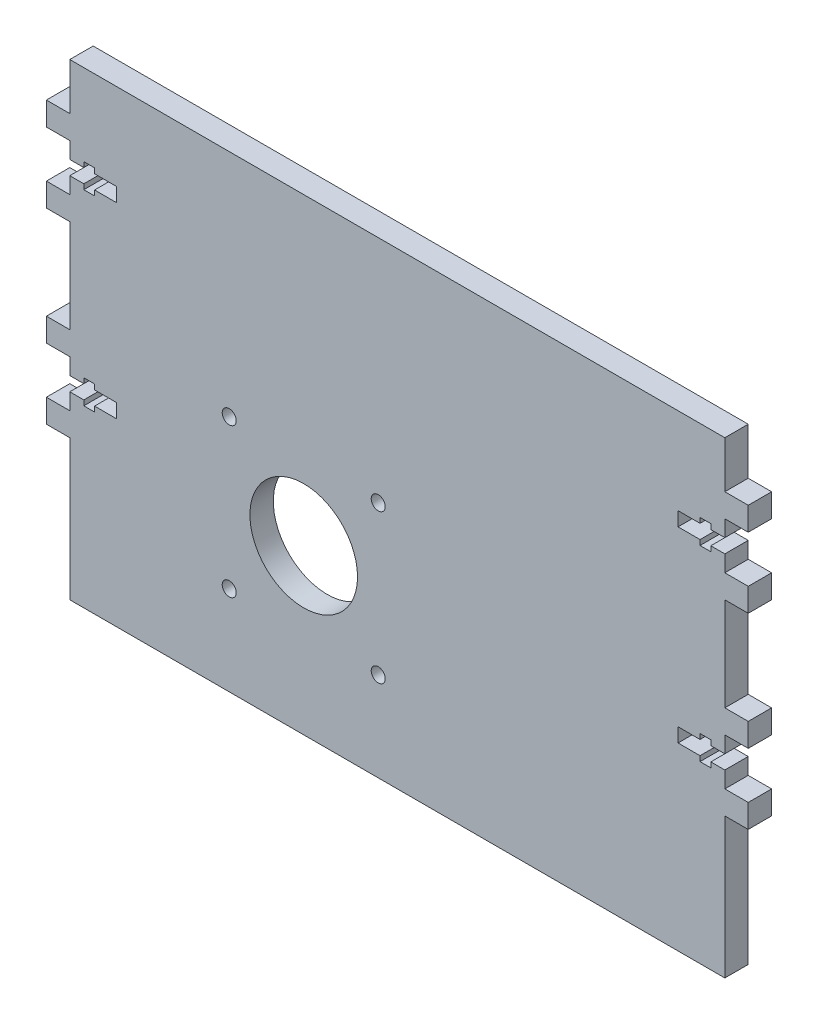
SolidWorks part; units mm, degrees
ref_plane "Front Plane" through (0, 0, 0) normal (0, 0, 1) x (1, 0, 0)
ref_plane "Top Plane" through (0, 0, 0) normal (0, 1, 0) x (1, 0, 0)
ref_plane "Right Plane" through (0, 0, 0) normal (1, 0, 0) x (0, 0, -1)
sketch "Sketch1" plane through (0, 0, 0) normal (0, 0, 1) x (1, 0, 0)
  line L0 (0, 0) -> (0, 100) construction
  line L1 (0, 100) -> (-140, 100)
  line L4 (-70, 68.7693) -> (-70, -10.9046) construction
  line L5 (0, 60) -> (-37.6147, 60) construction
  line L6 (0, 80) -> (-11.2208, 80) construction
  line L7 (0, 78.5) -> (0, 75)
  line L8 (5, 75) -> (5, 70)
  line L9 (5, 70) -> (0, 70)
  line L10 (5, 75) -> (0, 75)
  line L11 (0, 81.5) -> (0, 85)
  line L12 (0, 85) -> (5, 85)
  line L13 (5, 85) -> (5, 90)
  line L14 (5, 90) -> (0, 90)
  line L15 (0, 78.5) -> (0, 81.5) construction
  line L16 (0, 81.5) -> (-3, 81.5)
  line L17 (-5.3, 81.5) -> (-5.3, 82.6)
  line L18 (-3, 77.4) -> (-5.3, 77.4)
  line L19 (-3, 82.6) -> (-3, 81.5)
  line L20 (-5.3, 81.5) -> (-10, 81.5)
  line L21 (-10, 81.5) -> (-10, 78.5)
  line L22 (-10, 78.5) -> (-5.3, 78.5)
  line L23 (-3, 78.5) -> (-3, 77.4)
  line L24 (-5.3, 82.6) -> (-3, 82.6)
  line L25 (-5.3, 77.4) -> (-5.3, 78.5)
  line L26 (-3, 78.5) -> (0, 78.5)
  line L27 (-10, 80) -> (0, 80) construction
  line L66 (-145, 90) -> (-140, 90)
  line L67 (-145, 85) -> (-145, 90)
  line L68 (-140, 85) -> (-145, 85)
  line L69 (-140, 81.5) -> (-140, 85)
  line L70 (-140, 81.5) -> (-137, 81.5)
  line L71 (-137, 82.6) -> (-137, 81.5)
  line L72 (-134.7, 82.6) -> (-137, 82.6)
  line L73 (-134.7, 81.5) -> (-134.7, 82.6)
  line L74 (-134.7, 81.5) -> (-130, 81.5)
  line L75 (-130, 81.5) -> (-130, 78.5)
  line L76 (-130, 78.5) -> (-134.7, 78.5)
  line L77 (-134.7, 77.4) -> (-134.7, 78.5)
  line L78 (-137, 77.4) -> (-134.7, 77.4)
  line L79 (-137, 78.5) -> (-137, 77.4)
  line L80 (-137, 78.5) -> (-140, 78.5)
  line L81 (-140, 78.5) -> (-140, 75)
  line L82 (-145, 75) -> (-140, 75)
  line L83 (-145, 75) -> (-145, 70)
  line L84 (-145, 70) -> (-140, 70)
  line L85 (-140, 100) -> (-140, 90)
  line L90 (0, 90) -> (0, 100)
  line L91 (-145, 50) -> (-140, 50)
  line L92 (-145, 45) -> (-145, 50)
  line L93 (-145, 45) -> (-140, 45)
  line L94 (-140, 41.5) -> (-140, 45)
  line L95 (-137, 41.5) -> (-140, 41.5)
  line L96 (-137, 41.5) -> (-137, 42.6)
  line L97 (-137, 42.6) -> (-134.7, 42.6)
  line L98 (-134.7, 42.6) -> (-134.7, 41.5)
  line L99 (-130, 41.5) -> (-134.7, 41.5)
  line L100 (-130, 38.5) -> (-130, 41.5)
  line L101 (-134.7, 38.5) -> (-130, 38.5)
  line L102 (-134.7, 38.5) -> (-134.7, 37.4)
  line L103 (-134.7, 37.4) -> (-137, 37.4)
  line L104 (-137, 37.4) -> (-137, 38.5)
  line L105 (-140, 38.5) -> (-137, 38.5)
  line L106 (-140, 38.5) -> (-140, 35)
  line L107 (-140, 35) -> (-145, 35)
  line L108 (-145, 35) -> (-145, 30)
  line L109 (-145, 30) -> (-140, 30)
  line L110 (-140, 0) -> (-140, 30)
  line L111 (0, 0) -> (-140, 0)
  line L112 (0, 30) -> (0, 0)
  line L113 (5, 30) -> (0, 30)
  line L114 (5, 35) -> (5, 30)
  line L115 (0, 35) -> (5, 35)
  line L116 (0, 38.5) -> (0, 35)
  line L117 (0, 38.5) -> (-3, 38.5)
  line L118 (-3, 37.4) -> (-3, 38.5)
  line L119 (-5.3, 37.4) -> (-3, 37.4)
  line L120 (-5.3, 38.5) -> (-5.3, 37.4)
  line L121 (-5.3, 38.5) -> (-10, 38.5)
  line L122 (-10, 38.5) -> (-10, 41.5)
  line L123 (-10, 41.5) -> (-5.3, 41.5)
  line L124 (-5.3, 42.6) -> (-5.3, 41.5)
  line L125 (-3, 42.6) -> (-5.3, 42.6)
  line L126 (-3, 41.5) -> (-3, 42.6)
  line L127 (-3, 41.5) -> (0, 41.5)
  line L128 (0, 41.5) -> (0, 45)
  line L129 (5, 45) -> (0, 45)
  line L130 (5, 45) -> (5, 50)
  line L131 (5, 50) -> (0, 50)
  line L132 (-140, 70) -> (-140, 50)
  line L133 (0, 70) -> (0, 50)
  point P7 (0, 0)
  point P8 (-70, 79.6739)
  point P9 (0, 0)
  point P10 (0, 0)
  point P77 (0, 0)
  point P78 (0, 0)
  point P79 (0, 0)
  point P80 (-70, 44.6187)
  point P101 (0, 0)
  point P102 (0, 0)
  point P103 (-37.6147, 39.837)
  point P104 (0, 0)
  point P105 (0, 0)
  point P106 (0, 110.768)
  point P107 (0, 0)
  point P108 (0, 0)
  point P109 (-70, 38.5)
  point P110 (0, 0)
  circle B0 centre (-105.922, 50.922) radius 1.5
  circle B1 centre (-74.078, 50.922) radius 1.5
  circle B2 centre (-74.078, 19.078) radius 1.5
  circle B3 centre (-105.922, 19.078) radius 1.5
  circle B4 centre (-90, 35) radius 11.5
  dimension "D2" = 40
  dimension "D3" = 140
  dimension "D4" = 10
  dimension "D5" = 5
  dimension "D6" = 5
  dimension "D7" = 5.2
  dimension "D8" = 3
  dimension "D9" = 2.3
  dimension "D10" = 3
  dimension "D11" = 10
  dimension "D12" = 100
  dimension "D13" = 20
  dimension "D14" = 20
  dimension "D15" = 25
sketch_block_instance "Fixation Nema 17-1"
sketch_block "Fixation Nema 17"
extrude "Boss-Extrude1" add sketch "Sketch1" along normal blind 5
